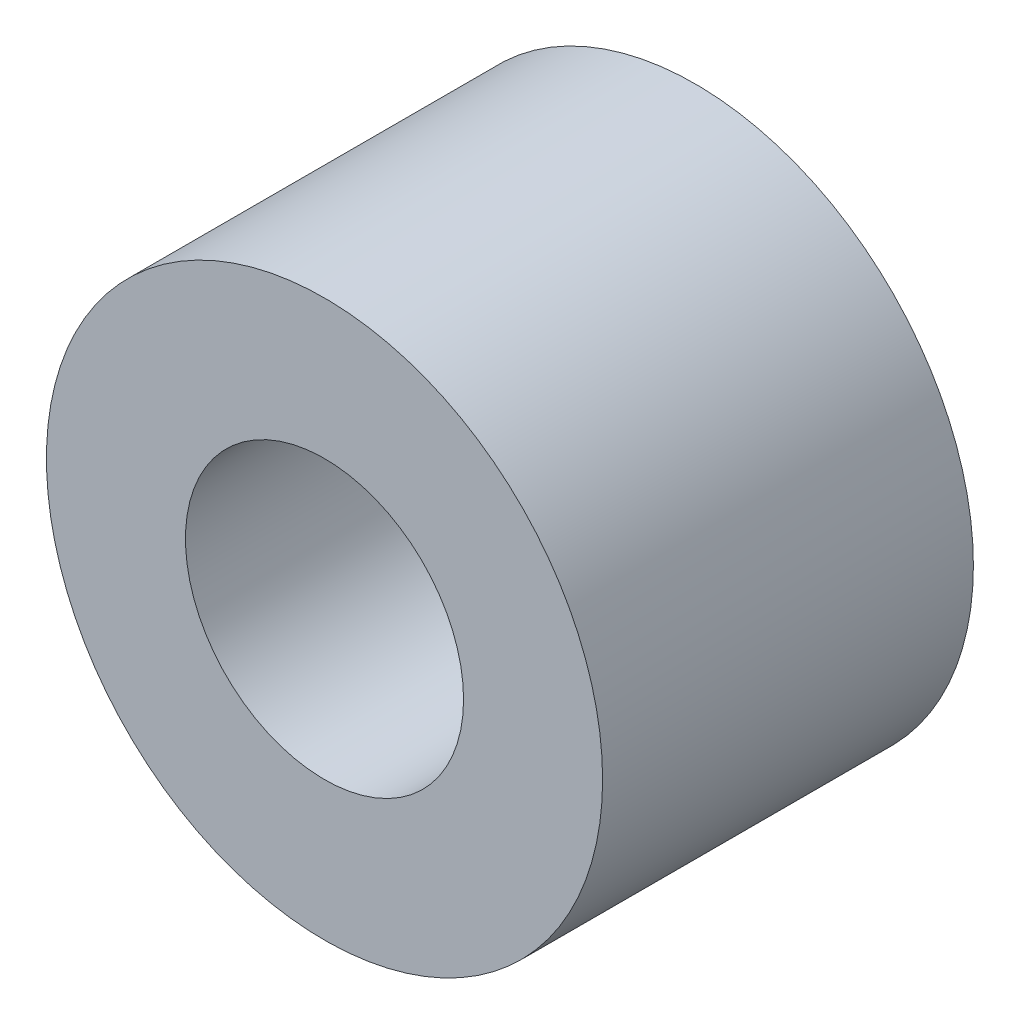
SolidWorks part; units mm, degrees
material "尼龙 101"
ref_plane "前视基准面" through (0, 0, 0) normal (0, 0, 1) x (1, 0, 0)
ref_plane "上视基准面" through (0, 0, 0) normal (0, 1, 0) x (1, 0, 0)
ref_plane "右视基准面" through (0, 0, 0) normal (1, 0, 0) x (0, 0, -1)
sketch "草图2" plane through (0, 0, 0) normal (0, 0, 1) x (1, 0, 0)
  circle A0 centre (-80, 0.003) radius 1.5
  circle A1 centre (-80, 0.003) radius 3
  circle A2 centre (-80, 0.003) radius 1.5 construction
  dimension "D1" = 3
  dimension "D2" = 6
extrude "凸台-拉伸1" add sketch "草图2" along normal blind 4
